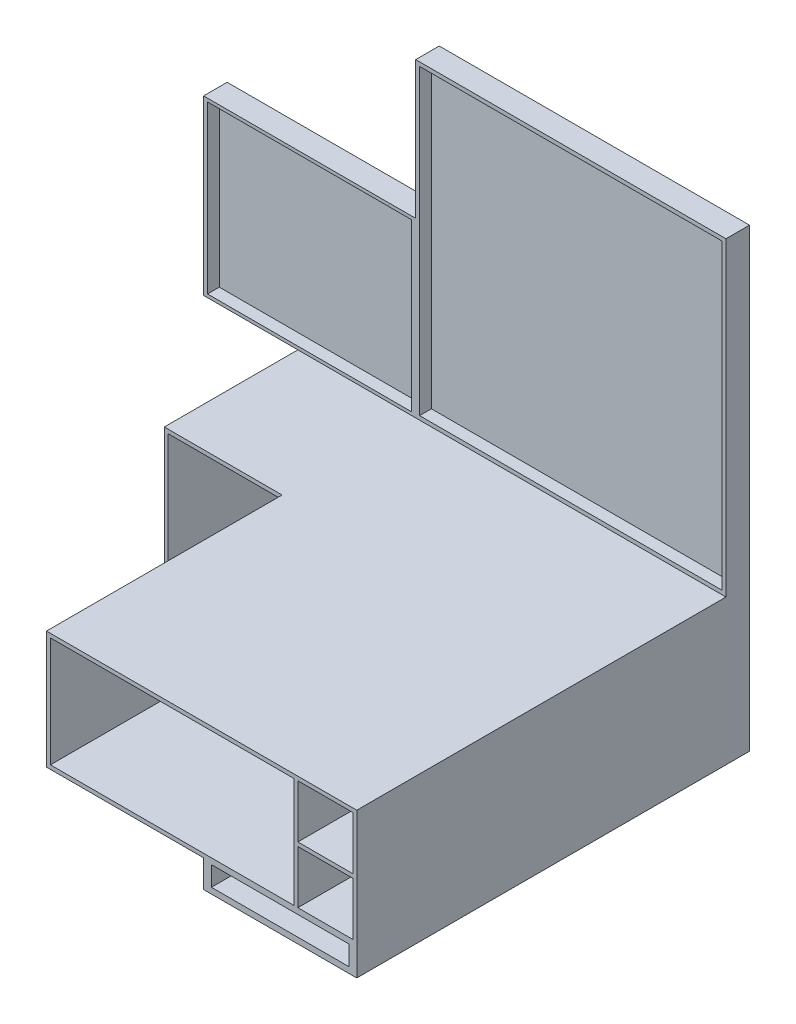
SolidWorks part; units mm, degrees
ref_plane "Front Plane" through (0, 0, 0) normal (0, 0, 1) x (1, 0, 0)
ref_plane "Top Plane" through (0, 0, 0) normal (0, 1, 0) x (1, 0, 0)
ref_plane "Right Plane" through (0, 0, 0) normal (1, 0, 0) x (0, 0, -1)
sketch "Sketch1" plane through (0, 0, 0) normal (0, 0, 1) x (1, 0, 0)
  line L1 (0, 0) -> (82, 0)
  line L2 (0, 0) -> (0, 82)
  line L3 (0, 82) -> (82, 82)
  line L4 (82, 0) -> (82, 82)
  dimension "D1" = 82
  dimension "D2" = 82
extrude "Boss-Extrude1" add sketch "Sketch1" along normal blind 6
sketch "Sketch2" plane through (0, 0, 6) normal (0, 0, 1) x (1, 0, 0)
  line L0 (82, 82) -> (0, 0) construction
  line L1 (0, 0) -> (0, 82) construction
  line L2 (0, 82) -> (82, 0) construction
  line L4 (1, 81) -> (81, 81)
  line L5 (1, 81) -> (1, 1)
  line L6 (1, 1) -> (81, 1)
  line L7 (81, 81) -> (81, 1)
  line L8 (1, 81) -> (81, 1) construction
  line L9 (1, 1) -> (81, 81) construction
  point P4 (41, 41)
  dimension "D1" = 80
extrude "Cut-Extrude1" cut sketch "Sketch2" against normal blind 3
sketch "Sketch3" plane through (0, 0, 0) normal (0, 0, -1) x (-1, 0, 0)
  line L1 (0, 0) -> (-82, 0)
  line L2 (0, 0) -> (0, -30)
  line L3 (0, -30) -> (-82, -30)
  line L4 (-82, 0) -> (-82, -30)
  dimension "D1" = 82
  dimension "D2" = 30
extrude "Boss-Extrude2" add sketch "Sketch3" against normal blind 100
sketch "Sketch4" plane through (0, 0, 100) normal (0, 0, 1) x (1, 0, 0)
  line L0 (0, 0) -> (82, -30) construction
  line L1 (82, -30) -> (82, 0) construction
  line L2 (82, 0) -> (0, -30) construction
  line L4 (1, -1) -> (81, -1)
  line L5 (1, -1) -> (1, -29)
  line L6 (1, -29) -> (81, -29)
  line L7 (81, -1) -> (81, -29)
  line L8 (1, -1) -> (81, -29) construction
  line L9 (1, -29) -> (81, -1) construction
  point P4 (41, -15)
  dimension "D1" = 80
  dimension "D2" = 28
extrude "Cut-Extrude2" cut sketch "Sketch4" against normal blind 97
sketch "Sketch5" plane through (0, 0, 0) normal (0, 0, -1) x (-1, 0, 0)
  line L1 (0, -30) -> (30, -30)
  line L2 (0, -30) -> (0, 0)
  line L3 (0, 0) -> (30, 0)
  line L4 (30, -30) -> (30, 0)
  dimension "D1" = 30
  dimension "D2" = 30
extrude "Boss-Extrude3" add sketch "Sketch5" against normal blind 40
sketch "Sketch6" plane through (0, 0, 40) normal (0, 0, 1) x (1, 0, 0)
  line L0 (0, 0) -> (-30, -30) construction
  line L1 (-30, -30) -> (-30, 0) construction
  line L2 (-30, 0) -> (0, -30) construction
  line L4 (-1, -29) -> (-29, -29)
  line L5 (-1, -29) -> (-1, -1)
  line L6 (-1, -1) -> (-29, -1)
  line L7 (-29, -29) -> (-29, -1)
  line L8 (-1, -29) -> (-29, -1) construction
  line L9 (-1, -1) -> (-29, -29) construction
  point P4 (-15, -15)
  dimension "D1" = 28
  dimension "D2" = 28
extrude "Cut-Extrude3" cut sketch "Sketch6" against normal blind 37
sketch "Sketch7" plane through (0, 0, 0) normal (0, 0, -1) x (-1, 0, 0)
  line L1 (0, 0) -> (57, 0)
  line L2 (0, 0) -> (0, 47)
  line L3 (0, 47) -> (57, 47)
  line L4 (57, 0) -> (57, 47)
  dimension "D1" = 57
  dimension "D2" = 47
extrude "Boss-Extrude4" add sketch "Sketch7" against normal blind 6
sketch "Sketch9" plane through (0, 0, 6) normal (0, 0, 1) x (1, 0, 0)
  line L0 (0, 0) -> (0, 47) construction
  line L1 (0, 47) -> (-57, 0) construction
  line L2 (-57, 0) -> (-57, 47) construction
  line L3 (-57, 47) -> (0, 0) construction
  line L5 (-56, 46.1754) -> (-1, 46.1754)
  line L6 (-56, 46.1754) -> (-56, 0.8246)
  line L7 (-56, 0.8246) -> (-1, 0.8246)
  line L8 (-1, 46.1754) -> (-1, 0.8246)
  line L9 (-56, 46.1754) -> (-1, 0.8246) construction
  line L10 (-56, 0.8246) -> (-1, 46.1754) construction
  point P4 (-28.5, 23.5)
  dimension "D1" = 55
  dimension "D2" = 45.3509
extrude "Cut-Extrude4" cut sketch "Sketch9" against normal blind 3
sketch "Sketch10" plane through (0, -30, 0) normal (0, -1, 0) x (-1, 0, 0)
  line L0 (-82, -100) -> (0, -100) construction
  line L1 (-82, 0) -> (-43, 0)
  line L2 (-82, 0) -> (-82, -100)
  line L3 (-82, -100) -> (-43, -100)
  line L4 (-43, 0) -> (-43, -100)
  dimension "D1" = 100
  dimension "D2" = 39
extrude "Boss-Extrude6" add sketch "Sketch10" along normal blind 7
sketch "Sketch12" plane through (0, 0, 100) normal (0, 0, 1) x (1, 0, 0)
  line L0 (43, -30) -> (43, -29) construction
  line L1 (1, -29) -> (81, -29) construction
  line L2 (43, -29) -> (82, -29) construction
  line L3 (82, 0) -> (82, -37) construction
  line L4 (82, -29) -> (43, -37) construction
  line L5 (43, -37) -> (82, -37) construction
  line L6 (82, -37) -> (43, -29) construction
  line L8 (45, -30.5) -> (80, -30.5)
  line L9 (45, -30.5) -> (45, -35.5)
  line L10 (45, -35.5) -> (80, -35.5)
  line L11 (80, -30.5) -> (80, -35.5)
  line L12 (45, -30.5) -> (80, -35.5) construction
  line L13 (45, -35.5) -> (80, -30.5) construction
  point P5 (62.5, -33)
  dimension "D1" = 35
  dimension "D2" = 5
extrude "Cut-Extrude5" cut sketch "Sketch12" against normal blind 97
sketch "Sketch13" plane through (0, 46.1754, 0) normal (0, -1, 0) x (1, 0, 0)
  line L1 (-1, 3) -> (-56, 3)
  line L2 (-1, 3) -> (-1, 6)
  line L3 (-1, 6) -> (-56, 6)
  line L4 (-56, 3) -> (-56, 6)
extrude "Boss-Extrude7" add sketch "Sketch13" along normal blind 3
sketch "Sketch14" plane through (-56, 0, 0) normal (1, 0, 0) x (0, 0, -1)
  line L1 (-3, 0.8246) -> (-6, 0.8246)
  line L2 (-3, 0.8246) -> (-3, 43.1754)
  line L3 (-3, 43.1754) -> (-6, 43.1754)
  line L4 (-6, 0.8246) -> (-6, 43.1754)
extrude "Boss-Extrude8" add sketch "Sketch14" along normal blind 3
sketch "Sketch15" plane through (-57, 0, 0) normal (-1, 0, 0) x (0, 0, 1)
  line L1 (0, 47) -> (6, 47)
  line L2 (0, 47) -> (0, 0)
  line L3 (0, 0) -> (6, 0)
  line L4 (6, 47) -> (6, 0)
extrude "Cut-Extrude6" cut sketch "Sketch15" against normal blind 3
sketch "Sketch16" plane through (0, 47, 0) normal (0, 1, 0) x (1, 0, 0)
  line L1 (-54, 0) -> (0, 0)
  line L2 (-54, 0) -> (-54, -6)
  line L3 (-54, -6) -> (0, -6)
  line L4 (0, 0) -> (0, -6)
extrude "Cut-Extrude7" cut sketch "Sketch16" against normal blind 3
sketch "Sketch17" plane through (81, 0, 0) normal (-1, 0, 0) x (0, 0, 1)
  line L1 (6, 81) -> (3, 81)
  line L2 (6, 81) -> (6, 1)
  line L3 (6, 1) -> (3, 1)
  line L4 (3, 81) -> (3, 1)
extrude "Boss-Extrude9" add sketch "Sketch17" along normal blind 3
sketch "Sketch18" plane through (0, 81, 0) normal (0, -1, 0) x (1, 0, 0)
  line L1 (78, 3) -> (1, 3)
  line L2 (78, 3) -> (78, 6)
  line L3 (78, 6) -> (1, 6)
  line L4 (1, 3) -> (1, 6)
extrude "Boss-Extrude10" add sketch "Sketch18" along normal blind 3
sketch "Sketch19" plane through (81, 0, 0) normal (-1, 0, 0) x (0, 0, 1)
  line L1 (3, -1) -> (100, -1)
  line L2 (3, -1) -> (3, -29)
  line L3 (3, -29) -> (100, -29)
  line L4 (100, -1) -> (100, -29)
extrude "Boss-Extrude11" add sketch "Sketch19" along normal blind 3
sketch "Sketch20" plane through (43, 0, 0) normal (-1, 0, 0) x (0, 0, 1)
  line L1 (0, -30) -> (100, -30)
  line L2 (0, -30) -> (0, -37)
  line L3 (0, -37) -> (100, -37)
  line L4 (100, -30) -> (100, -37)
extrude "Boss-Extrude12" add sketch "Sketch20" along normal blind 3
sketch "Sketch21" plane through (45, 0, 0) normal (1, 0, 0) x (0, 0, -1)
  line L1 (-3, -30.5) -> (-100, -30.5)
  line L2 (-3, -30.5) -> (-3, -35.5)
  line L3 (-3, -35.5) -> (-100, -35.5)
  line L4 (-100, -30.5) -> (-100, -35.5)
extrude "Cut-Extrude8" cut sketch "Sketch21" against normal blind 3
sketch "Sketch22" plane through (80, 0, 0) normal (-1, 0, 0) x (0, 0, 1)
  line L1 (3, -30.5) -> (100, -30.5)
  line L2 (3, -30.5) -> (3, -35.5)
  line L3 (3, -35.5) -> (100, -35.5)
  line L4 (100, -30.5) -> (100, -35.5)
extrude "Boss-Extrude13" add sketch "Sketch22" along normal blind 3
sketch "Sketch23" plane through (82, 0, 0) normal (1, 0, 0) x (0, 0, -1)
  line L1 (-100, -37) -> (0, -37)
  line L2 (-100, -37) -> (-100, 82)
  line L3 (-100, 82) -> (0, 82)
  line L4 (0, -37) -> (0, 82)
extrude "Cut-Extrude9" cut sketch "Sketch23" against normal blind 3
sketch "Sketch24" plane through (0, 82, 0) normal (0, 1, 0) x (1, 0, 0)
  line L1 (0, 0) -> (79, 0)
  line L2 (0, 0) -> (0, -6)
  line L3 (0, -6) -> (79, -6)
  line L4 (79, 0) -> (79, -6)
extrude "Cut-Extrude10" cut sketch "Sketch24" against normal blind 3
sketch "Sketch25" plane through (0, 0, 3) normal (0, 0, 1) x (1, 0, 0)
  line L0 (78, -1) -> (64, -1) construction
  line L1 (78, -1) -> (1, -1) construction
  line L2 (1, -29) -> (78, -29) construction
  line L3 (64, -1) -> (62, -1)
  line L4 (64, -1) -> (64, -29)
  line L5 (64, -29) -> (62, -29)
  line L6 (62, -1) -> (62, -29)
  dimension "D1" = 14
  dimension "D2" = 2
extrude "Boss-Extrude14" add sketch "Sketch25" along normal blind 97
sketch "Sketch26" plane through (0, 0, 3) normal (0, 0, 1) x (1, 0, 0)
  line L0 (76.6552, -15) -> (70.5, -15) construction
  line L1 (78, -1) -> (78, -29) construction
  line L2 (64, -29) -> (64, -1) construction
  line L3 (77, -14.5) -> (64, -14.5)
  line L4 (77, -14.5) -> (77, -15.5)
  line L5 (77, -15.5) -> (64, -15.5)
  line L6 (64, -14.5) -> (64, -15.5)
  line L7 (77, -14.5) -> (64, -15.5) construction
  line L8 (77, -15.5) -> (64, -14.5) construction
  line L10 (77, -14.5) -> (78, -14.5)
  line L11 (77, -14.5) -> (77, -15.5)
  line L12 (77, -15.5) -> (78, -15.5)
  line L13 (78, -14.5) -> (78, -15.5)
  line M4 (64, -1) -> (64, -29)
  line M6 (78, -29) -> (78, -1)
  dimension "D2" = 1
extrude "Boss-Extrude16" add sketch "Sketch26" along normal blind 97 contours L5 L4 L3 M4 | L4 L12 L10 M6
sketch "Sketch31" plane through (62, 0, 0) normal (-1, 0, 0) x (0, 0, 1)
  line L1 (3, -1) -> (100, -1)
  line L2 (3, -1) -> (3, -29)
  line L3 (3, -29) -> (100, -29)
  line L4 (100, -1) -> (100, -29)
extrude "Cut-Extrude11" cut sketch "Sketch31" against normal blind 1
